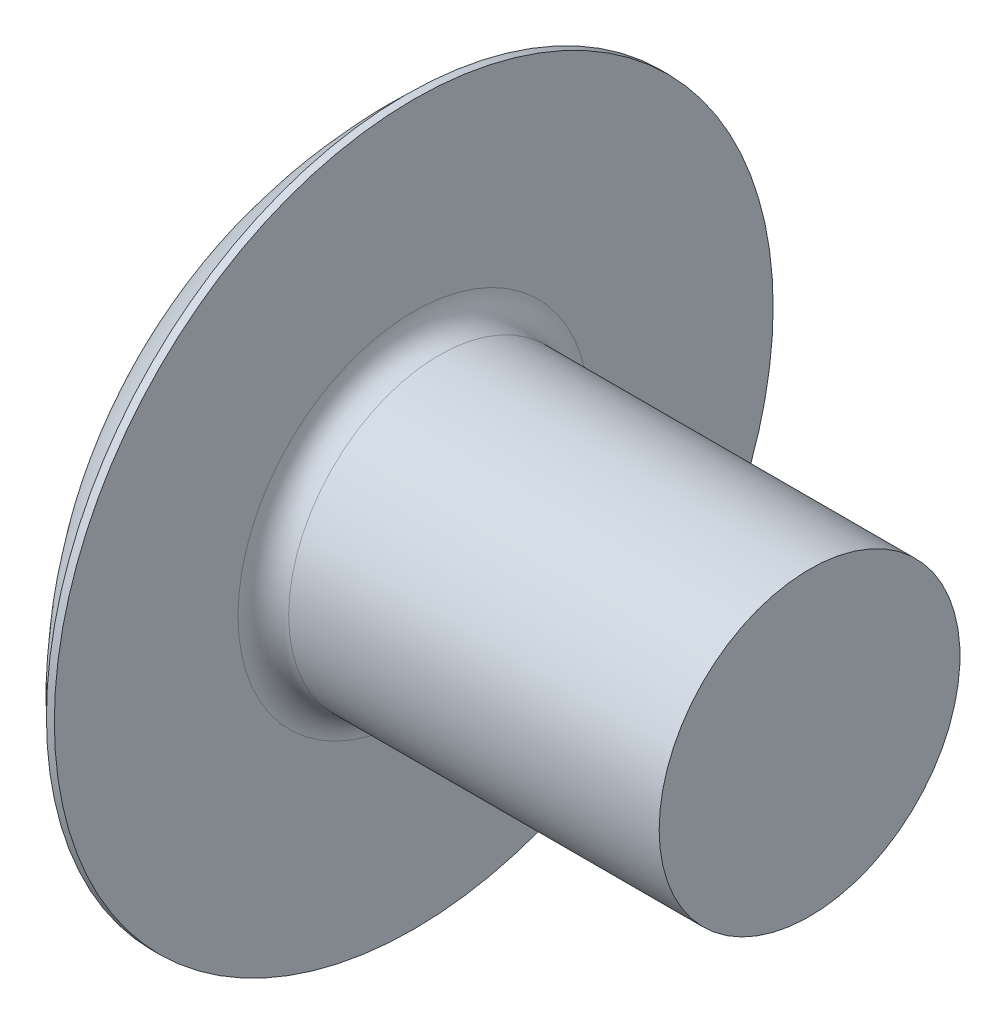
SolidWorks part; units mm, degrees
ref_plane "Plane1" through (0, 0, 0) normal (0, 0, 1) x (1, 0, 0)
ref_plane "Plane2" through (0, 0, 0) normal (0, 1, 0) x (1, 0, 0)
ref_plane "Plane3" through (0, 0, 0) normal (1, 0, 0) x (0, 0, -1)
sketch "BodySke" plane through (0, 0, 0) normal (0, 0, 1) x (1, 0, 0)
  line L0 (0, 0) -> (8.9916, 0)
  line L1 (3.048, 2.413) -> (8.9916, 2.413)
  line L2 (2.6416, -2.413) -> (8.9916, -2.413) construction
  line L3 (8.9916, 2.413) -> (8.9916, 0)
  line L4 (2.6416, -5.7658) -> (2.5146, -5.7658) construction
  line L5 (2.6416, 5.7658) -> (2.5146, 5.7658)
  line L6 (0, 0) -> (123.825, 0) construction
  line L7 (3.7008, 19.05) -> (3.7008, -3.175) construction
  line L8 (2.6416, 5.7658) -> (2.6416, 2.8194)
  line L9 (2.6416, 19.05) -> (2.6416, -6.35) construction
  arc A0 (2.5146, 5.7658) -> (0, 0) centre (7.8676, 0) ccw
  arc A1 (3.048, 2.413) -> (2.6416, 2.8194) centre (3.048, 2.8194) cw
  point P11 (2.6416, 2.413)
  dimension "Fillet_radius" = 0.4064
  dimension "Diameter" = 4.826
  dimension "Head_ht" = 2.6416
  dimension "Length" = 6.35
  dimension "Head_dia" = 11.5316
  dimension "D1" = 0.127
  dimension "Advance" = 1.0592
  dimension "Thread_nom" = 6.35
revolve "Base-Revolve" add sketch "BodySke" angle 360 about L6
cosmetic thread "ThreadCosmetic" [suppressed] parameters "Thread_length"=5.2908, "Thread_minor"=3.5662
sketch "ThdSchSke" plane through (0, 0, 0) normal (0, 0, 1) x (1, 0, 0)
  line L0 (3.7008, -1.7831) -> (3.2597, -2.413)
  line L1 (3.7008, -1.7831) -> (4.1419, -2.413)
  line L2 (4.1419, -2.413) -> (4.1419, -3.0163)
  line L3 (-3.175, 0) -> (5.1513, 0) construction
  line L5 (4.1419, -3.0163) -> (3.2597, -3.0163)
  line L6 (3.2597, -3.0163) -> (3.2597, -2.413)
  point P6 (0, 0)
  dimension "Diameter" = 4.826
  dimension "SideAngle" = 55
  dimension "VeeAngle" = 70
  dimension "Thread_minor" = 3.5662
  dimension "Overcut" = 6.0325
  dimension "Start" = 3.7008
revolve "ThreadSchematic" [suppressed] cut sketch "ThdSchSke" angle 360 about L3
pattern_linear "ThdSchPat" [suppressed]
equation "\"Thread_length@ThreadCosmetic\" = ((sgn( (\"Length@BodySke\" - \"Advance@BodySke\" ) - \"Thread_nom@BodySke\" )-1)*( (\"Length@BodySke\" - \"Advance@BodySke\" ) - \"Thread_nom@BodySke\" ))/-2+ \"Thread_nom@BodySke\""
equation "\"Thread_minor@ThdSchSke\" = \"Thread_minor@ThreadCosmetic\""
equation "\"Diameter@ThdSchSke\" = \"Diameter@BodySke\""
equation "\"Overcut@ThdSchSke\" = \"Diameter@BodySke\" * 1.25"
equation "\"Start@ThdSchSke\" = \"Head_ht@BodySke\" + \"Length@BodySke\" - \"Thread_length@ThreadCosmetic\"  '---Non-countersunk---"
equation "\"Num_threads@ThdSchPat\" = int( \"Thread_length@ThreadCosmetic\" / \"Advance@BodySke\" + 0.999 )  + 1"
equation "\"Advance@ThdSchPat\" = \"Thread_length@ThreadCosmetic\" /  (\"Num_threads@ThdSchPat\" - 1) 'relax it"
